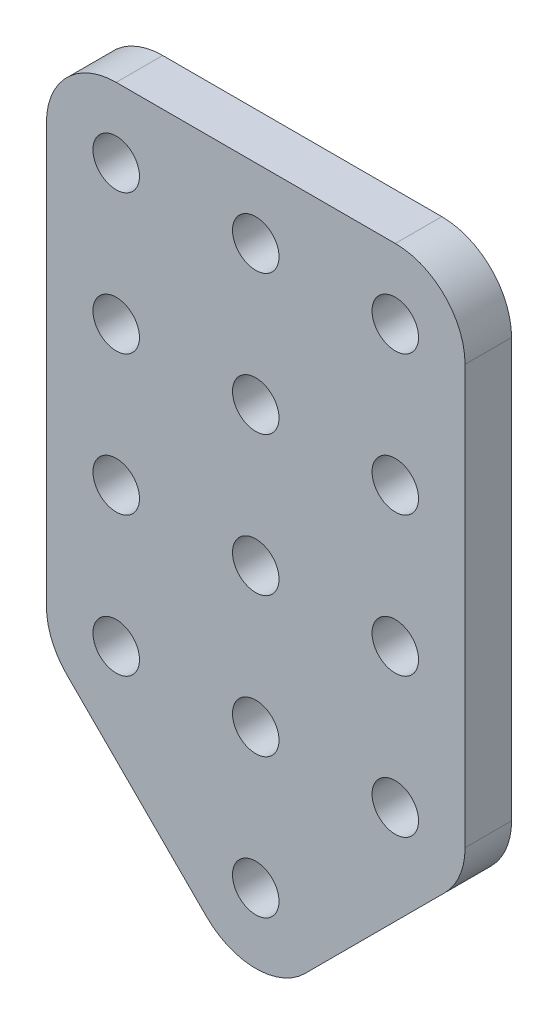
SolidWorks part; units mm, degrees
ref_plane "Alzado" through (0, 0, 0) normal (0, 0, 1) x (1, 0, 0)
ref_plane "Planta" through (0, 0, 0) normal (0, 1, 0) x (1, 0, 0)
ref_plane "Vista lateral" through (0, 0, 0) normal (1, 0, 0) x (0, 0, -1)
sketch "Model" plane through (0, 0, 0) normal (0, 0, 1) x (1, 0, 0)
  line L0 (174.2271, 213.1787) -> (174.2271, 204.1787)
  line L1 (174.2271, 213.1787) -> (174.2271, 231.1787)
  line L2 (201.2271, 231.1787) -> (201.2271, 204.1787)
  line L3 (190.909, 191.9967) -> (199.909, 200.9967)
  line L4 (184.5451, 191.9967) -> (175.5451, 200.9967)
  line L5 (196.7271, 235.6787) -> (178.7271, 235.6787)
  circle A0 centre (187.7271, 204.1787) radius 1.5
  circle A1 centre (178.7271, 204.1787) radius 1.5
  circle A2 centre (187.7271, 213.1787) radius 1.5
  circle A3 centre (178.7271, 213.1787) radius 1.5
  circle A4 centre (196.7271, 213.1787) radius 1.5
  circle A5 centre (187.7271, 195.1787) radius 1.5
  circle A6 centre (196.7271, 204.1787) radius 1.5
  arc A7 (184.5451, 191.9967) -> (190.909, 191.9967) centre (187.7271, 195.1787) ccw
  arc A8 (199.909, 200.9967) -> (201.2271, 204.1787) centre (196.7271, 204.1787) ccw
  arc A9 (174.2271, 204.1787) -> (175.5451, 200.9967) centre (178.7271, 204.1787) ccw
  circle A10 centre (187.7271, 222.1787) radius 1.5
  circle A11 centre (178.7271, 222.1787) radius 1.5
  circle A12 centre (196.7271, 222.1787) radius 1.5
  circle A13 centre (187.7271, 231.1787) radius 1.5
  circle A14 centre (178.7271, 231.1787) radius 1.5
  circle A15 centre (196.7271, 231.1787) radius 1.5
  arc A16 (201.2271, 231.1787) -> (196.7271, 235.6787) centre (196.7271, 231.1787) ccw
  arc A17 (178.7271, 235.6787) -> (174.2271, 231.1787) centre (178.7271, 231.1787) ccw
extrude "Saliente-Extruir1" add sketch "Model" along normal blind 3
